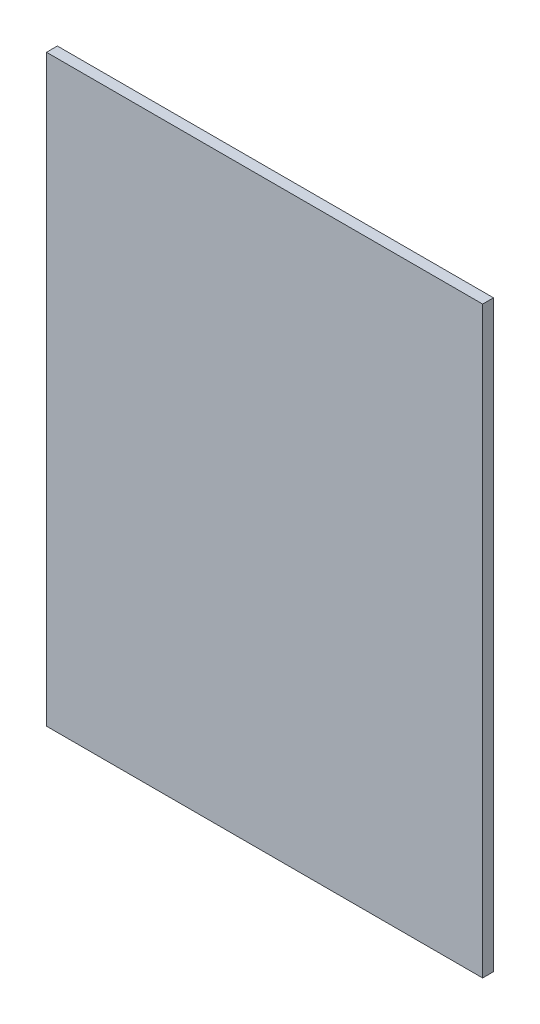
SolidWorks part; units mm, degrees
material "Oak"
ref_plane "Front Plane" through (0, 0, 0) normal (0, 0, 1) x (1, 0, 0)
ref_plane "Top Plane" through (0, 0, 0) normal (0, 1, 0) x (1, 0, 0)
ref_plane "Right Plane" through (0, 0, 0) normal (1, 0, 0) x (0, 0, -1)
sketch "Sketch1" plane through (0, 0, 0) normal (0, 0, 1) x (1, 0, 0)
  line L1 (0, 0) -> (510.54, 0)
  line L2 (0, 0) -> (0, 683.26)
  line L3 (0, 683.26) -> (510.54, 683.26)
  line L4 (510.54, 0) -> (510.54, 683.26)
  dimension "D1" = 683.26
  dimension "D2" = 510.54
extrude "Boss-Extrude1" add sketch "Sketch1" along normal blind 12.7
